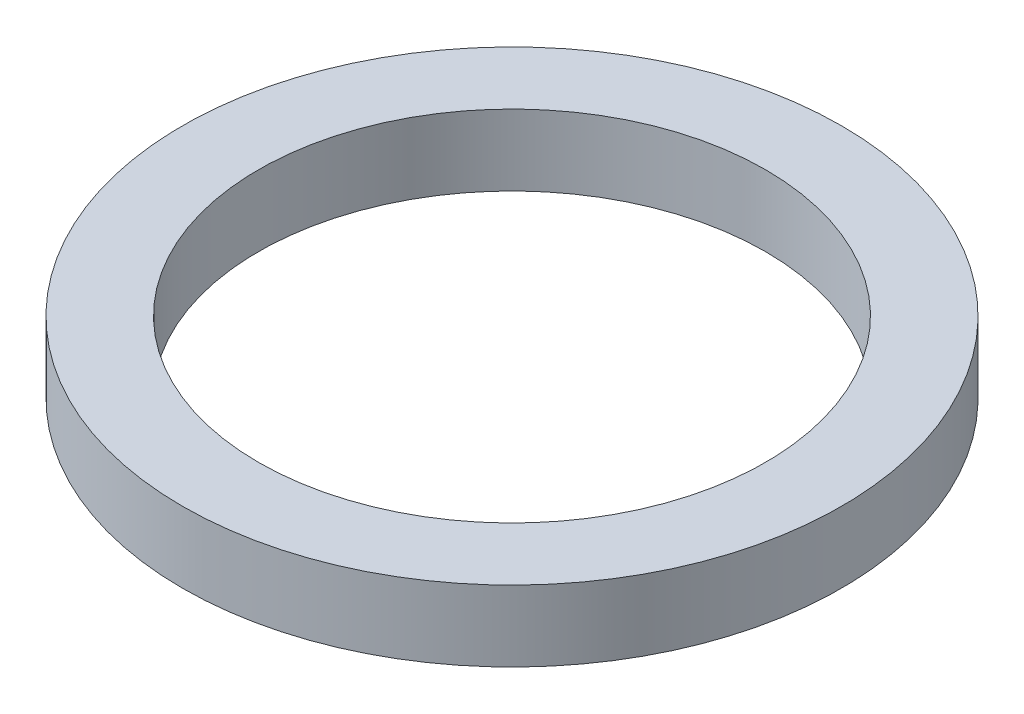
SolidWorks part; units mm, degrees
ref_plane "Front Plane" through (0, 0, 0) normal (0, 0, 1) x (1, 0, 0)
ref_plane "Top Plane" through (0, 0, 0) normal (0, 1, 0) x (1, 0, 0)
ref_plane "Right Plane" through (0, 0, 0) normal (1, 0, 0) x (0, 0, -1)
sketch "Sketch1" plane through (0, 0, 0) normal (0, 1, 0) x (1, 0, 0)
  circle A0 centre (0, 0) radius 25
  circle A1 centre (0, 0) radius 32.5
  dimension "D1" = 50
  dimension "D2" = 65
extrude "Boss-Extrude1" add sketch "Sketch1" along normal mid plane 7
equation "\"Nr\" = 123"
equation "\"module\" = 0.5"
equation "\"pressure_angle\" = 20.0"
equation "\"h_a\" = 0.5"
equation "\"h_f\" = 0.625"
equation "\"clr_tip_root\" = 0.125"
equation "\"dp_r\" = 61.5"
equation "\"db_r\" = 57.79109617833337"
equation "\"fw_r\" = 8.0"
equation "\"alpha_r\" = 0.8539582918412414"
equation "\"beta_r\" = 3.171331217828824"
equation "\"bearing_ID\" = 50"
equation "\"bearing_OD\" = 65"
equation "\"bearing_height\" = 7"
equation "\"clearance_planet\" = 1.5"
equation "\"case_dist\" = 6.5"
equation "\"Motor_case_OD_max\" = 96.5"
equation "\"case_mounting_PCD\" = 89.0"
equation "\"bearing mount thickness\" = 8"
equation "\"case_mounting_hole_dia\" = 3"
equation "\"output_mounting_PCD\" = 73"
equation "\"output_mounting_hole_dia\" = 4"
equation "\"clearance_case_mount_holes_shell_thickness\" = 1"
equation "\"motor_case_OD_base\" = 87.0"
equation "\"sec_carrier_thickness\" = 5"
equation "\"sun_coupler_hub_thickness\" = 4"
equation "\"clearance_sun_coupler_sec_carrier\" = 1.5"
equation "\"clearance_motor_and_case\" = 5"
equation "\"motor_OD\" = 72"
equation "\"Motor_case_thickness\" = 2.5"
equation "\"Motor_case_ID\" = 82"
equation "\"case_mounting_hole_shift\" = 1.0"
equation "\"output_mounting_nut_wrench_size\" = 7"
equation "\"output_mounting_nut_thickness\" = 3.2"
equation "\"case_mounting_hole_allen_socket_dia\" = 5.5"
equation "\"output_mounting_nut_depth\" = 3"
equation "\"case_mounting_bolt_depth\" = 4.5"
equation "\"Ns\" = 33"
equation "\"Np\" = 45"
equation "\"ring_radial_thickness\" = 5"
equation "\"ring_OD\" = 71.5"
equation "\"ring_to_chamfer_clearance\" = 2"
equation "\"Motor_case_OD_base_to_chamfer\" = 5"
equation "\"pattern_offset_from_motor_case_OD_base\" = 3"
equation "\"pattern_bulge_dia\" = 3"
equation "\"pattern_num_bulge\" = 18"
equation "\"pattern_depth\" = 2"
equation "\"motor_height\" = 27"
equation "\"case_mounting_wrench_size\" = 5.5"
equation "\"case_mounting_nut_clearance\" = 2"
equation "\"base_plate_thickness\" = 4"
equation "\"case_mounting_nut_thickness\" = 2.4"
equation "\"case_mounting_surface_height\" = 4"
equation "\"motor_mount_hole_PCD\" = 32"
equation "\"motor_mount_hole_dia\" = 4"
equation "\"motor_mount_hole_num\" = 4"
equation "\"central_hole_offset_from_motor_mount_PCD\" = 5"
equation "\"wire_slot_dist_from_center\" = 30"
equation "\"wire_slot_length\" = 10"
equation "\"wire_slot_radius\" = 2.5"
equation "\"driver_upper_holes_dist_from_center\" = 23"
equation "\"driver_lower_holes_dist_from_center\" = 15"
equation "\"driver_side_holes_dist_from_center\" = 20"
equation "\"driver_mount_holes_dia\" = 2.5"
equation "\"driver_mount_inserts_OD\" = 3.5"
equation "\"driver_mount_thickness\" = 1.5"
equation "\"driver_mount_height\" = 4"
equation "\"air_flow_hole_offset\" = 3"
equation "\"num_planet\" = 3"
equation "\"planet_pin_bolt_dia\" = 5"
equation "\"planet_pin_socket_head_dia\" = 8.5"
equation "\"carrier_PCD\" = 39.0"
equation "\"planet_shaft_dia\" = 8"
equation "\"fw_p\" = 8.0"
equation "\"planet_shaft_step_offset\" = 1"
equation "\"carrier_trapezoidal_support_sun_offset\" = 5"
equation "\"carrier_trapezoidal_support_hole_PCD_offset_bearing_ID\" = 4"
equation "\"carrier_trapezoidal_support_hole_dia\" = 3"
equation "\"carrier_trapezoidal_support_hole_socket_head_dia\" = 5.5"
equation "\"carrier_bearing_step_width\" = 1.5"
equation "\"standard_clearance_1_5mm\" = 1.5"
equation "\"standard_fillet_1_5mm\" = 1.5"
equation "\"sun_shaft_bearing_OD\" = 16"
equation "\"sun_shaft_bearing_width\" = 5"
equation "\"standard_bearing_insertion_chamfer\" = 0.5"
equation "\"D1@Sketch1\"=\"bearing_ID\""
equation "\"D2@Sketch1\"=\"bearing_OD\""
equation "\"D1@Boss-Extrude1\"=\"bearing_height\""
equation "\"D7@Sketch2\"=\"carrier_trapezoidal_support_hole_dia\""
equation "\"D5@Sketch2\"= 360 / ( 4 * \"Ns\" ) - \"alpha_s\""
equation "\"D3@Sketch2\"=\"dp_s\"- 2*\"h_b\""
equation "\"D9@Sketch2\"=\"carrier_trapezoidal_support_sun_offset\""
equation "\"carrier_trapezoidal_support_hole_wrench_size\" = 5.5"
equation "\"planet_pin_bolt_wrench_size\" = 8"
equation "\"pressure angle\" = 20.0"
equation "\"motor_output_hole_PCD\" = 22"
equation "\"motor_output_hole_dia\" = 3"
equation "\"motor_output_hole_num\" = 4"
equation "\"h_b\" = 0.625"
equation "\"dp_s\" = 16.5"
equation "\"db_s\" = 15.50492824296749"
equation "\"fw_s_calc\" = 1.2595130854287364"
equation "\"alpha_s\" = 0.8539582918412449"
equation "\"beta_s\" = 3.7466288708629643"
equation "\"dp_p\" = 22.5"
equation "\"db_p\" = 21.14308396768294"
equation "\"alpha_p\" = 0.8539582918412307"
equation "\"beta_p\" = 2.2920834163175385"
equation "\"planet_bearing_OD\" = 12"
equation "\"planet_bearing_width\" = 3.5"
equation "\"planet_bore\" = 10"
equation "\"sun_shaft_bearing_ID\" = 8"
equation "\"sun_hub_dia\" = 31.0"
equation "\"sun_central_bolt_dia\" = 5"
equation "\"sun_central_bolt_socket_head_dia\" = 8.5"
equation "\"fw_s_used\" = 16.0"
equation "\"motor_output_hole_CSK_OD\" = 6"
equation "\"motor_output_hole_CSK_head_height\" = 1.5"
equation "\"bearing_retainer_thickness\" = 2"
